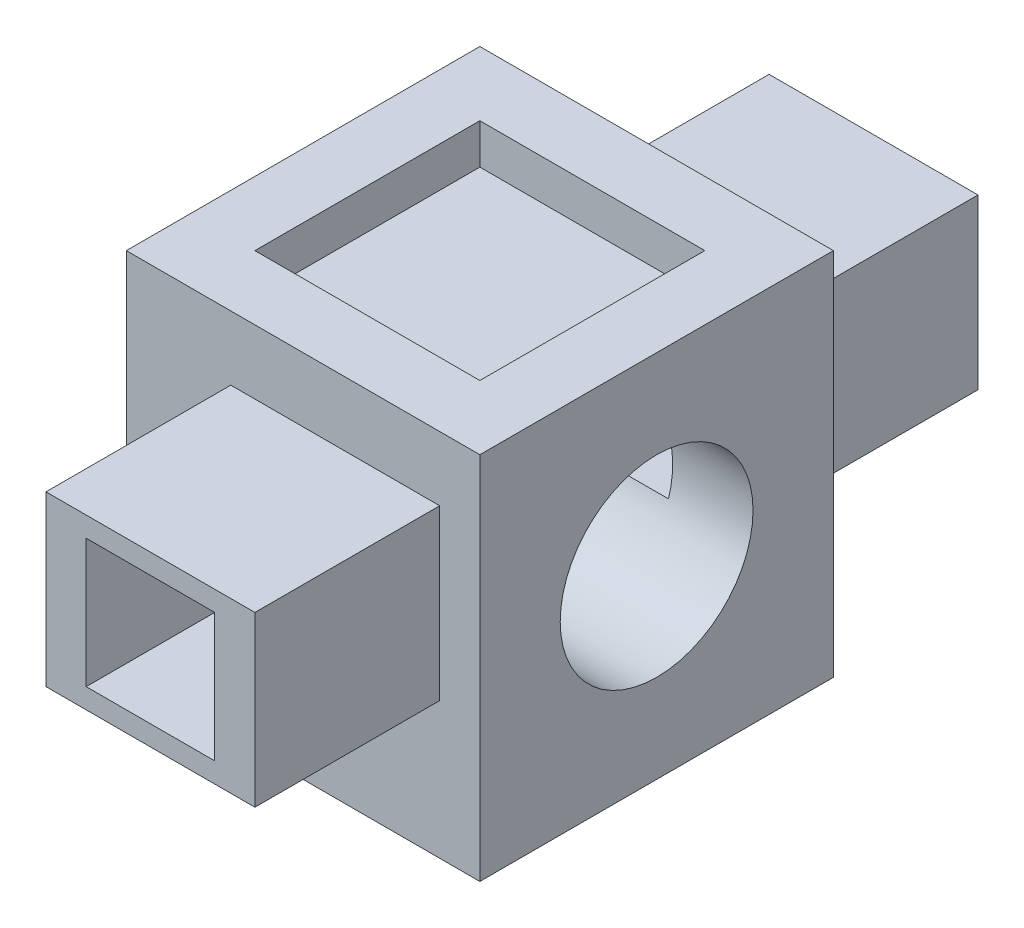
SolidWorks part; units mm, degrees
ref_plane "Front Plane" through (0, 0, 0) normal (0, 0, 1) x (1, 0, 0)
ref_plane "Top Plane" through (0, 0, 0) normal (0, 1, 0) x (1, 0, 0)
ref_plane "Right Plane" through (0, 0, 0) normal (1, 0, 0) x (0, 0, -1)
sketch "Sketch1" plane through (0, 0, 0) normal (0, 0, 1) x (1, 0, 0)
  line L1 (0, 0) -> (44, 0)
  line L2 (0, 0) -> (0, 46)
  line L3 (0, 46) -> (44, 46)
  line L4 (44, 0) -> (44, 46)
  dimension "D1" = 44
  dimension "D2" = 46
extrude "Boss-Extrude1" add sketch "Sketch1" along normal mid plane 44
sketch "Sketch4" plane through (0, 0, 22) normal (0, 0, 1) x (1, 0, 0)
  line L0 (44, 46) -> (0, 46) construction
  line L1 (13, 17) -> (39, 17)
  line L2 (13, 17) -> (13, 38)
  line L3 (13, 38) -> (39, 38)
  line L4 (39, 17) -> (39, 38)
  line L5 (0, 46) -> (0, 0) construction
  dimension "D1" = 8
  dimension "D2" = 13
  dimension "D3" = 21
  dimension "D4" = 26
extrude "Boss-Extrude3" add sketch "Sketch4" along normal blind 23 and the other way blind 67
sketch "Sketch5" plane through (0, 0, 45) normal (0, 0, 1) x (1, 0, 0)
  line L0 (39, 17) -> (13, 17) construction
  line L3 (18, 35.5) -> (34, 35.5)
  line L4 (34, 35.5) -> (34, 19.5)
  line L5 (34, 19.5) -> (18, 19.5)
  line L6 (39, 17) -> (39, 38) construction
  line L7 (18, 35.5) -> (18, 19.5)
  point P17 (26, 35.5)
  point P18 (18, 27.5)
  dimension "D1" = 16
  dimension "D2" = 16
  dimension "D3" = 2.5
  dimension "D4" = 5
extrude "Cut-Extrude1" cut sketch "Sketch5" against normal through all and the other way through all
sketch "Sketch6" plane through (44, 0, 0) normal (1, 0, 0) x (0, 0, -1)
  line L0 (-22, 46) -> (22, 46) construction
  circle A0 centre (0, 23) radius 12
  dimension "D1" = 24
  dimension "D2" = 23
extrude "Cut-Extrude2" cut sketch "Sketch6" against normal up to vertex (44 mm away) up to point (0, 0, 0)
sketch "Sketch7" plane through (0, 46, 0) normal (0, 1, 0) x (1, 0, 0)
  line L0 (44, -22) -> (0, -22) construction
  line L1 (36, -14) -> (8, -14)
  line L2 (36, -14) -> (36, 14)
  line L3 (36, 14) -> (8, 14)
  line L4 (8, -14) -> (8, 14)
  point P0 (8, 0)
  point P11 (0, 0)
  point P12 (0, 0)
  dimension "D1" = 28
  dimension "D2" = 28
  dimension "D3" = 8
  dimension "D4" = 8
extrude "Cut-Extrude3" cut sketch "Sketch7" against normal blind 5
